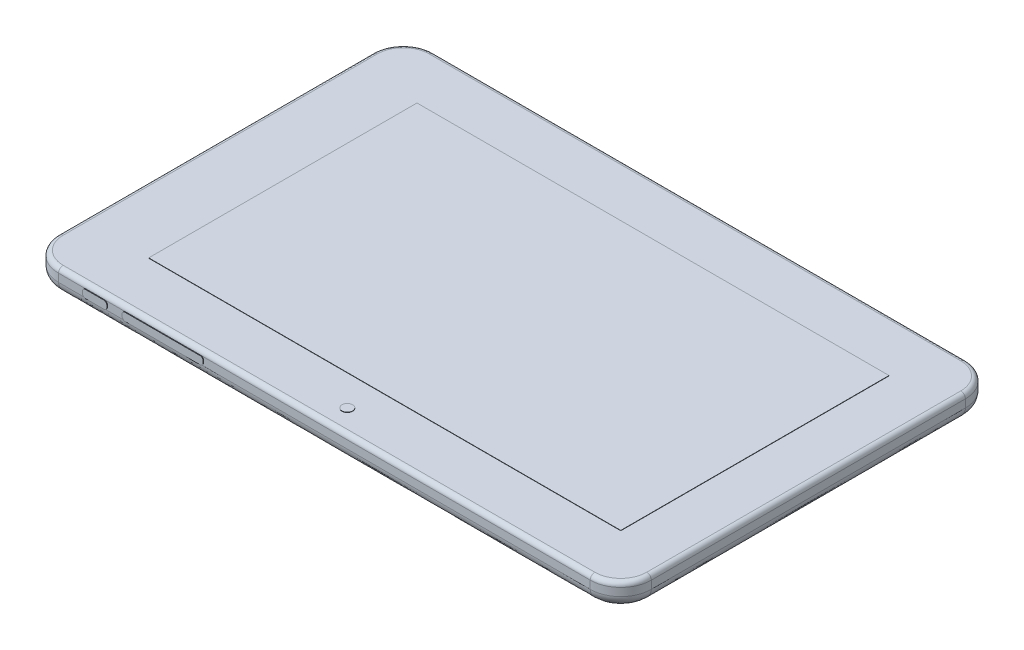
SolidWorks part; units mm, degrees
ref_plane "Płaszczyzna przednia" through (0, 0, 0) normal (0, 0, 1) x (1, 0, 0)
ref_plane "Płaszczyzna górna" through (0, 0, 0) normal (0, 1, 0) x (1, 0, 0)
ref_plane "Płaszczyzna prawa" through (0, 0, 0) normal (1, 0, 0) x (0, 0, -1)
sketch "Szkic1" plane through (0, 0, 0) normal (0, 1, 0) x (1, 0, 0)
  line L0 (-45.648, -1126.3229) -> (-45.648, -1229.1229)
  line L1 (-35.648, -1239.1229) -> (138.352, -1239.1229)
  line L2 (148.352, -1229.1229) -> (148.352, -1126.3229)
  line L3 (138.352, -1116.3229) -> (-35.648, -1116.3229)
  arc A0 (138.352, -1239.1229) -> (148.352, -1229.1229) centre (138.352, -1229.1229) ccw
  arc A1 (-45.648, -1229.1229) -> (-35.648, -1239.1229) centre (-35.648, -1229.1229) ccw
  arc A2 (-45.648, -1126.3229) -> (-35.648, -1116.3229) centre (-35.648, -1126.3229) cw
  arc A3 (148.352, -1126.3229) -> (138.352, -1116.3229) centre (138.352, -1126.3229) ccw
  dimension "D3" = 10
  dimension "D1" = 194
  dimension "D2" = 122.8
extrude "Dodanie-wyciągnięcie1" add sketch "Szkic1" along normal blind 10.1
ref_plane "Płaszczyzna1" through (-35.648, 0, 0) normal (-1, 0, 0) x (0, 0, 1)
sketch "Szkic3" plane through (0, 10.1, 0) normal (0, 1, 0) x (1, 0, 0)
  line L0 (138.352, -1116.3229) -> (-35.648, -1116.3229) construction
  line L1 (148.352, -1229.1229) -> (148.352, -1126.3229) construction
  line L2 (-35.648, -1239.1229) -> (138.352, -1239.1229) construction
  line L3 (-45.648, -1126.3229) -> (-45.648, -1229.1229) construction
  line L4 (138.352, -1116.3229) -> (-35.648, -1116.3229)
  line L5 (148.352, -1229.1229) -> (148.352, -1126.3229)
  line L6 (-35.648, -1239.1229) -> (138.352, -1239.1229)
  line L7 (-45.648, -1126.3229) -> (-45.648, -1229.1229)
  arc A0 (148.352, -1126.3229) -> (138.352, -1116.3229) centre (138.352, -1126.3229) ccw construction
  arc A1 (138.352, -1239.1229) -> (148.352, -1229.1229) centre (138.352, -1229.1229) ccw construction
  arc A2 (-45.648, -1229.1229) -> (-35.648, -1239.1229) centre (-35.648, -1229.1229) ccw construction
  arc A3 (-35.648, -1116.3229) -> (-45.648, -1126.3229) centre (-35.648, -1126.3229) ccw construction
  arc A4 (148.352, -1126.3229) -> (138.352, -1116.3229) centre (138.352, -1126.3229) ccw
  arc A5 (138.352, -1239.1229) -> (148.352, -1229.1229) centre (138.352, -1229.1229) ccw
  arc A6 (-45.648, -1229.1229) -> (-35.648, -1239.1229) centre (-35.648, -1229.1229) ccw
  arc A7 (-35.648, -1116.3229) -> (-45.648, -1126.3229) centre (-35.648, -1126.3229) ccw
sketch "Szkic2" plane through (-35.648, 0, 0) normal (-1, 0, 0) x (0, 0, 1)
  line L0 (1116.3229, 10.1) -> (1116.3229, 8.6)
  line L1 (1116.3229, 10.1) -> (1116.3229, 0) construction
  line L2 (1116.3229, 10.1) -> (1117.8229, 10.1)
  arc A0 (1116.3229, 8.6) -> (1117.8229, 10.1) centre (1117.8229, 8.6) cw
  dimension "D1" = 1.5
  dimension "D2" = 1.5
sweep "Wycięcie-wyciągnięcie po ścieżce1" cut profiles "Szkic2" path "Szkic3"
sketch "Szkic4" plane through (0, 0, 0) normal (0, -1, 0) x (1, 0, 0)
  line L4 (138.352, 1239.1229) -> (-35.648, 1239.1229)
  line L5 (-45.648, 1229.1229) -> (-45.648, 1126.3229)
  line L6 (-35.648, 1116.3229) -> (138.352, 1116.3229)
  line L7 (148.352, 1126.3229) -> (148.352, 1229.1229)
  line L8 (138.352, 1239.1229) -> (-35.648, 1239.1229)
  line L9 (-45.648, 1229.1229) -> (-45.648, 1126.3229)
  line L10 (-35.648, 1116.3229) -> (138.352, 1116.3229)
  line L11 (148.352, 1126.3229) -> (148.352, 1229.1229)
  arc A4 (148.352, 1229.1229) -> (138.352, 1239.1229) centre (138.352, 1229.1229) ccw
  arc A5 (-35.648, 1239.1229) -> (-45.648, 1229.1229) centre (-35.648, 1229.1229) ccw
  arc A6 (-45.648, 1126.3229) -> (-35.648, 1116.3229) centre (-35.648, 1126.3229) ccw
  arc A7 (138.352, 1116.3229) -> (148.352, 1126.3229) centre (138.352, 1126.3229) ccw
  arc A8 (148.352, 1229.1229) -> (138.352, 1239.1229) centre (138.352, 1229.1229) ccw
  arc A9 (-35.648, 1239.1229) -> (-45.648, 1229.1229) centre (-35.648, 1229.1229) ccw
  arc A10 (-45.648, 1126.3229) -> (-35.648, 1116.3229) centre (-35.648, 1126.3229) ccw
  arc A11 (138.352, 1116.3229) -> (148.352, 1126.3229) centre (138.352, 1126.3229) ccw
  dimension "D1" = 0
sketch "Szkic5" plane through (-35.648, 0, 0) normal (-1, 0, 0) x (0, 0, 1)
  line L0 (1116.3229, 0) -> (1116.3229, 6)
  line L1 (1116.3229, 8.6) -> (1116.3229, 0) construction
  line L2 (1116.3229, 0) -> (1126.3229, 0)
  spline S0 degree 2 poles (1116.3229, 6) (1116.4486, 1.5614) (1126.3229, 0) knots 0 0 0 1 1 1
  dimension "D1" = 10
  dimension "D2" = 6
sweep "Wycięcie-wyciągnięcie po ścieżce2" cut profiles "Szkic5" path "Szkic4"
sketch "Szkic6" plane through (0, 0, 1239.1229) normal (0, 0, 1) x (1, 0, 0)
  line L0 (-26.648, 8.6) -> (-20.648, 8.6)
  line L1 (-27.648, 7.6) -> (-27.648, 7)
  line L2 (-19.648, 7.6) -> (-19.648, 7)
  line L3 (-26.648, 6) -> (-20.648, 6)
  line L4 (138.352, 8.6) -> (-35.648, 8.6) construction
  line L6 (-45.648, 8.6) -> (-45.648, 6) construction
  arc A0 (-27.648, 7) -> (-26.648, 6) centre (-26.648, 7) ccw
  arc A1 (-27.648, 7.6) -> (-26.648, 8.6) centre (-26.648, 7.6) cw
  arc A2 (-20.648, 8.6) -> (-19.648, 7.6) centre (-20.648, 7.6) cw
  arc A3 (-19.648, 7) -> (-20.648, 6) centre (-20.648, 7) cw
  point P12 (-27.648, 8.6)
  point P15 (-19.648, 8.6)
  dimension "D4" = 1
  dimension "D1" = 8
  dimension "D2" = 2.6
  dimension "D3" = 18
sketch "Szkic7" plane through (0, 0, 1239.1229) normal (0, 0, 1) x (1, 0, 0)
  line L0 (-13.648, 8.6) -> (10.852, 8.6)
  line L1 (-14.648, 7.6) -> (-14.648, 7)
  line L2 (11.852, 7.6) -> (11.852, 7)
  line L3 (-13.648, 6) -> (10.852, 6)
  line L4 (138.352, 8.6) -> (-35.648, 8.6) construction
  line L6 (-45.648, 8.6) -> (-45.648, 6) construction
  arc A0 (-14.648, 7.6) -> (-13.648, 8.6) centre (-13.648, 7.6) cw
  arc A1 (-14.648, 7) -> (-13.648, 6) centre (-13.648, 7) ccw
  arc A2 (11.852, 7) -> (10.852, 6) centre (10.852, 7) cw
  arc A3 (10.852, 8.6) -> (11.852, 7.6) centre (10.852, 7.6) cw
  point P10 (-14.648, 8.6)
  point P17 (11.852, 8.6)
  dimension "D4" = 1
  dimension "D1" = 2.6
  dimension "D2" = 26.5
  dimension "D3" = 31
extrude "Dodanie-wyciągnięcie2" add sketch "Szkic6" along normal blind 0.2
extrude "Dodanie-wyciągnięcie3" add sketch "Szkic7" along normal blind 0.2
sketch "Szkic8" plane through (-45.648, 0, 0) normal (-1, 0, 0) x (0, 0, 1)
  line L0 (1151.1229, 8.6) -> (1157.1229, 8.6)
  line L1 (1150.1229, 7.6) -> (1150.1229, 7)
  line L2 (1158.1229, 7.6) -> (1158.1229, 7)
  line L3 (1151.1229, 6) -> (1157.1229, 6)
  line L4 (1229.1229, 8.6) -> (1126.3229, 8.6) construction
  line L5 (1239.1229, 8.6) -> (1239.1229, 6) construction
  arc A0 (1150.1229, 7) -> (1151.1229, 6) centre (1151.1229, 7) ccw
  arc A1 (1150.1229, 7.6) -> (1151.1229, 8.6) centre (1151.1229, 7.6) cw
  arc A2 (1158.1229, 7) -> (1157.1229, 6) centre (1157.1229, 7) cw
  arc A3 (1157.1229, 8.6) -> (1158.1229, 7.6) centre (1157.1229, 7.6) cw
  point P12 (1150.1229, 8.6)
  point P17 (1158.1229, 8.6)
  dimension "D4" = 1
  dimension "D1" = 2.6
  dimension "D2" = 8
  dimension "D3" = 81
extrude "Wytnij-wyciągnięcie1" cut sketch "Szkic8" against normal blind 5
sketch "Szkic9" plane through (0, 10.1, 0) normal (0, 1, 0) x (1, 0, 0)
  line L0 (-45.648, -1229.1229) -> (-45.648, -1157.1229) construction
  line L1 (138.352, -1239.1229) -> (10.852, -1239.1229) construction
  circle A0 centre (51.352, -1231.6229) radius 1.75
  dimension "D3" = 3.5
  dimension "D1" = 97
  dimension "D2" = 7.5
sketch "Szkic10" plane through (0, 10.1, 0) normal (0, 1, 0) x (1, 0, 0)
  line L0 (130.852, -1133.8229) -> (-23.648, -1133.8229)
  line L1 (130.852, -1133.8229) -> (130.852, -1221.6229)
  line L2 (-23.648, -1133.8229) -> (-23.648, -1221.6229)
  line L3 (130.852, -1221.6229) -> (-23.648, -1221.6229)
  line L4 (148.352, -1126.3229) -> (148.352, -1229.1229) construction
  line L5 (138.352, -1239.1229) -> (10.852, -1239.1229) construction
  line L6 (138.352, -1116.3229) -> (-35.648, -1116.3229) construction
  line L7 (-45.648, -1229.1229) -> (-45.648, -1157.1229) construction
  dimension "D1" = 17.5
  dimension "D2" = 17.5
  dimension "D3" = 17.5
  dimension "D4" = 22
extrude "Dodanie-wyciągnięcie4" add sketch "Szkic10" along normal blind 0.1
extrude "Dodanie-wyciągnięcie5" add sketch "Szkic9" along normal blind 0.1
